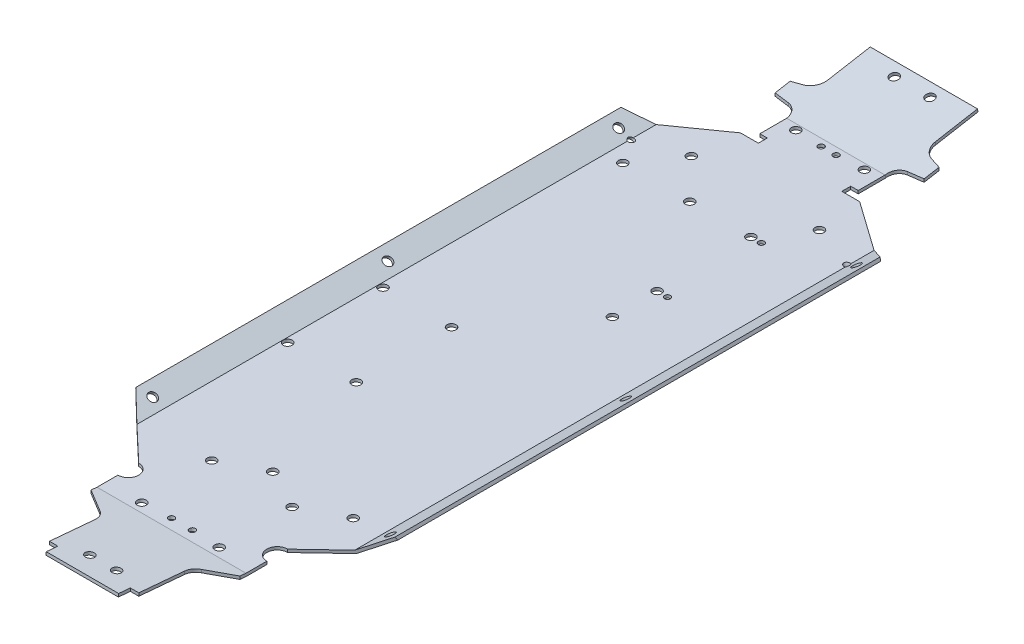
SolidWorks part; units mm, degrees
ref_plane "Front Plane" through (0, 0, 0) normal (0, 0, 1) x (1, 0, 0)
ref_plane "Top Plane" through (0, 0, 0) normal (0, 1, 0) x (1, 0, 0)
ref_plane "Right Plane" through (0, 0, 0) normal (1, 0, 0) x (0, 0, -1)
sketch "Sketch1" plane through (0, 0, 0) normal (0, 0, 1) x (1, 0, 0)
  line L0 (0, 0) -> (7.1603, -4.134)
  line L1 (7.1603, -4.134) -> (80.8397, -4.134)
  line L2 (80.8397, -4.134) -> (88, 0)
  line L3 (0.5, 0.866) -> (7.4282, -3.134)
  line L4 (7.4282, -3.134) -> (80.5718, -3.134)
  line L5 (80.5718, -3.134) -> (87.5, 0.866)
  line L6 (0, 0) -> (0.5, 0.866)
  line L7 (88, 0) -> (87.5, 0.866)
  dimension "D1" = 88
  dimension "D3" = 5
  dimension "D4" = 150
  dimension "D2" = 1
extrude "Boss-Extrude1" add sketch "Sketch1" along normal blind 197
sketch "Sketch3" plane through (0, -3.134, 0) normal (0, 1, 0) x (1, 0, 0)
  line L0 (24, 0) -> (44, 0) construction
  line L1 (0, -179) -> (0, -17)
  line L2 (88, -17) -> (64, 0)
  line L3 (0, -197) -> (0, 0) construction
  line L4 (88, -17) -> (44, -17) construction
  line L5 (44, 3.5664) -> (44, -208.1457) construction
  line L6 (0, -17) -> (24, 0)
  line L7 (24, 0) -> (64, 0)
  line L8 (0, -179) -> (19, -197)
  line L9 (80.5718, -197) -> (7.4282, -197) construction
  line L10 (88, -179) -> (88, -17)
  line L11 (88, -197) -> (88, 0) construction
  line L12 (19, -197) -> (69, -197)
  line L13 (88, -179) -> (69, -197)
  line L14 (0, -17) -> (0, 0)
  line L15 (80.5718, 0) -> (7.4282, 0) construction
  line L17 (0, 0) -> (24, 0)
  line L18 (88, 0) -> (64, 0)
  line L19 (88, 0) -> (88, -17)
  line L20 (0, -179) -> (0, -197)
  line L21 (0, -197) -> (19, -197)
  line L22 (69, -197) -> (88, -197)
  line L23 (88, -197) -> (88, -179)
  point P26 (44, -197)
  line M5 (80.5718, 0) -> (7.4282, 0)
  line M6 (7.4282, 0) -> (7.4282, -197)
  line M7 (7.4282, -197) -> (80.5718, -197)
  line M8 (80.5718, -197) -> (80.5718, 0)
  dimension "D2" = 20
  dimension "D3" = 17
  dimension "D4" = 43.5
  dimension "D5" = 18
  dimension "D6" = 25
extrude "Cut-Extrude3" cut sketch "Sketch3" against normal through all both and the other way through all contours L17 L14 L6 M6 | L6 M6 M5 | L2 M8 M5 | L19 L18 L2 M8 | L20 L21 L8 M6 | L8 M6 M7 | L13 M8 M7 | L22 L23 L13 M8
sketch "Sketch5" plane through (0, 0, 0) normal (1, 0, 0) x (0, 0, -1)
  line L0 (0, -3.134) -> (12, -3.134)
  line L1 (12, -3.134) -> (41.5442, 2.0755)
  line L2 (0, -4.134) -> (12.0875, -4.134)
  line L3 (12.0875, -4.134) -> (41.7179, 1.0907)
  line L4 (0, -3.134) -> (0, -4.134)
  line L5 (41.5442, 2.0755) -> (41.7179, 1.0907)
  dimension "D1" = 12
  dimension "D2" = 170
  dimension "D3" = 30
  dimension "D4" = 1
extrude "Boss-Extrude2" add sketch "Sketch5" along normal up to vertex (88 mm away) up to point (88, -3.134, 0)
sketch "Sketch6" plane through (0, -3.134, 0) normal (0, 1, 0) x (1, 0, 0)
  line L6 (24, 0) -> (30, 0)
  line L7 (24, 0) -> (-1.3455, 0)
  line L9 (44, 41.5442) -> (44, 3.5664) construction
  line L10 (88, 41.7179) -> (0, 41.7179) construction
  line L12 (88, 12.0875) -> (0, 12.0875) construction
  line L31 (30, 0) -> (30, 3)
  line L32 (30, 3) -> (27.5, 3)
  line L33 (27.5, 3) -> (27.5, 12.0875)
  line L34 (23.966, 16.0603) -> (19, 16.6427)
  line L35 (19, 16.6427) -> (19, 21.6427)
  line L36 (19, 21.6427) -> (22.3667, 22.5994)
  line L37 (26, 27.409) -> (26, 41.7179)
  line L38 (24, 0) -> (30, 0)
  line L39 (-1.3455, 0) -> (-1.3455, 57.6061)
  line L40 (-1.3455, 57.6061) -> (89.3455, 57.6061)
  line L41 (44, 41.7179) -> (44, 57.6061)
  line L42 (26, 41.7179) -> (62, 41.7179)
  line L43 (89.3455, 0) -> (89.3455, 57.6061)
  line L44 (64, 0) -> (58, 0)
  line L45 (62, 27.409) -> (62, 41.7179)
  line L46 (69, 21.6427) -> (65.6333, 22.5994)
  line L47 (69, 16.6427) -> (69, 21.6427)
  line L48 (64.034, 16.0603) -> (69, 16.6427)
  line L49 (60.5, 3) -> (60.5, 12.0875)
  line L50 (58, 3) -> (60.5, 3)
  line L51 (58, 0) -> (58, 3)
  line L52 (64, 0) -> (89.3455, 0)
  line L53 (64, 0) -> (58, 0)
  arc A4 (27.5, 12.0875) -> (23.966, 16.0603) centre (23.5, 12.0875) ccw
  arc A5 (22.3667, 22.5994) -> (26, 27.409) centre (21, 27.409) ccw
  arc A6 (65.6333, 22.5994) -> (62, 27.409) centre (67, 27.409) cw
  arc A7 (60.5, 12.0875) -> (64.034, 16.0603) centre (64.5, 12.0875) cw
  point P36 (44, 41.7179)
  dimension "D3" = 5
  dimension "D7" = 5
  dimension "D4" = 4
  dimension "D1" = 3
  dimension "D2" = 2.5
  dimension "D5" = 5
  dimension "D6" = 14
  dimension "D8" = 18
  dimension "D9" = 25
  dimension "D10" = 3.5
extrude "Cut-Extrude4" cut sketch "Sketch6" against normal through all both and the other way through all
sketch "Sketch8" plane through (0, 0, 0) normal (1, 0, 0) x (0, 0, -1)
  line L0 (-197, -3.134) -> (-211, -3.134)
  line L1 (-211, -3.134) -> (-240.8858, -0.5193)
  line L2 (-197, -4.134) -> (-211.0437, -4.134)
  line L3 (-211.0437, -4.134) -> (-240.973, -1.5155)
  line L4 (-197, -3.134) -> (-197, -4.134)
  line L5 (-240.8858, -0.5193) -> (-240.973, -1.5155)
  dimension "D1" = 30
  dimension "D2" = 175
  dimension "D3" = 14
  dimension "D4" = 1
extrude "Boss-Extrude3" add sketch "Sketch8" along normal up to vertex (88 mm away) up to point (88, -3.134, 179)
sketch "Sketch9" plane through (0, -3.134, 0) normal (0, 1, 0) x (1, 0, 0)
  line L0 (29, -221.6085) -> (29, -236.973)
  line L1 (19, -204) -> (19, -213)
  line L4 (27, -218) -> (19, -213)
  line L5 (29, -236.973) -> (31.8498, -236.973)
  line L6 (31.8498, -236.973) -> (31.8498, -240.973)
  line L7 (88, -240.8858) -> (0, -240.8858) construction
  line L8 (0, -197) -> (19, -197) construction
  line L9 (0, -197) -> (19, -197)
  line L10 (0, -197) -> (0, -211) construction
  line L11 (0, -197) -> (0, -211)
  line L12 (88, -240.973) -> (0, -240.973) construction
  line L13 (0, -211) -> (0, -240.8858) construction
  line L14 (56.1502, -240.8858) -> (31.8498, -240.8858)
  line L15 (0, -211) -> (0, -240.8858)
  line L16 (44, -240.8858) -> (44, -190.0299) construction
  line L18 (88, -211) -> (88, -240.8858)
  line L19 (88, -197) -> (88, -211)
  line L20 (88, -197) -> (69, -197)
  line L21 (56.1502, -236.973) -> (56.1502, -240.973)
  line L22 (59, -236.973) -> (56.1502, -236.973)
  line L23 (61, -218) -> (69, -213)
  line L24 (69, -204) -> (69, -213)
  line L25 (59, -221.6085) -> (59, -236.973)
  line L26 (0, -252.0171) -> (31.8498, -252.0171)
  line L27 (31.8498, -252.0171) -> (31.8498, -240.973)
  line L28 (0, -240.8858) -> (0, -252.0171)
  line L29 (56.1502, -240.973) -> (56.1502, -252.0171)
  line L30 (56.1502, -252.0171) -> (88, -252.0171)
  line L31 (88, -252.0171) -> (88, -240.8858)
  arc A0 (19, -197) -> (19, -204) centre (19, -200.5) cw
  arc A1 (27, -218) -> (29, -221.6085) centre (24.7447, -221.6085) cw
  arc A2 (61, -218) -> (59, -221.6085) centre (63.2553, -221.6085) ccw
  arc A3 (69, -197) -> (69, -204) centre (69, -200.5) ccw
  point P13 (44, -240.8858)
  point P29 (44, -240.8858)
  line M14 (19, -197) -> (0, -197)
  line M15 (0, -197) -> (0, -211)
  line M16 (0, -211) -> (88, -211)
  line M17 (88, -211) -> (88, -197)
  line M18 (88, -197) -> (69, -197)
  dimension "D1" = 3.5
  dimension "D2" = 9
  dimension "D3" = 8
  dimension "D4" = 5
  dimension "D5" = 15
  dimension "D6" = 12.1502
  dimension "D7" = 4
extrude "q" cut sketch "Sketch9" against normal through all both and the other way through all contours L23 A2 L25 L22 L21 L14 L18 L24 M16 | A3 L24 M18 M16 M17 | A1 L4 L1 L15 L14 L6 L5 L0 M16 | A0 L1 M14 M15 M16
sketch "Sketch11" plane through (0, -22.4262, 1.962) normal (0, -0.9962, 0.0872) x (1, 0, 0)
  line L0 (44, 241.7717) -> (44, 200.7065) construction
  line L3 (56.1502, 239.9239) -> (31.8498, 239.9239) construction
  line L4 (25.3426, 205.4239) -> (62.1457, 205.4239) construction
  circle A0 centre (39.5, 232.9239) radius 1.5
  circle A3 centre (31, 206.9239) radius 1.5
  circle A4 centre (40.5, 206.4239) radius 1
  circle A5 centre (47.5, 206.4239) radius 1
  circle A6 centre (57, 206.9239) radius 1.5
  circle A7 centre (48.5, 232.9239) radius 1.5
  point P8 (40.5, 206.4589)
  point P19 (44, 239.9239)
  dimension "D1" = 3
  dimension "D2" = 2
  dimension "D5" = 33
  dimension "D6" = 13
  dimension "D7" = 3.5
  dimension "D3" = 4.5
  dimension "D4" = 7
extrude "Cut-Extrude5" cut sketch "Sketch11" against normal blind 10
sketch "Sketch12" plane through (0, 0, 0) normal (-0.5, -0.866, 0) x (0.866, -0.5, 0)
  line L1 (4.134, 14.4641) -> (4.134, 182.3917) construction
  line L2 (0, 17) -> (8.2679, 11.9282) construction
  line L3 (0, 179) -> (8.2679, 185.7834) construction
  line L4 (8.2679, 185.7834) -> (8.2679, 11.9282) construction
  line L5 (0, 179) -> (0, 17) construction
  line L6 (0, 179) -> (0, 17)
  line L7 (4.134, 19.4641) -> (9.7158, 19.4641) construction
  line L9 (8.2679, 185.7834) -> (0, 179)
  line L10 (0, 179) -> (0, 17)
  line L11 (0, 17) -> (8.2679, 11.9282)
  line L12 (8.2679, 11.9282) -> (8.2679, 185.7834)
  line L13 (8.2679, 185.7834) -> (0, 179)
  line L14 (0, 179) -> (0, 17)
  line L15 (0, 17) -> (8.2679, 11.9282)
  line L16 (8.2679, 11.9282) -> (8.2679, 185.7834)
  circle A0 centre (4.134, 177.3917) radius 1.5
  circle A1 centre (4.134, 98.4279) radius 1.5
  circle A2 centre (4.134, 20.9641) radius 1.5
  circle A3 centre (8.2679, 20.4641) radius 1
  point P8 (8.2679, 20.4384)
  point P12 (4.134, 14.4641)
  point P15 (4.134, 182.3917)
  point P20 (0, 98)
  dimension "D1" = 3
  dimension "D2" = 5
  dimension "D3" = 5
  dimension "D5" = 2
  dimension "D4" = 0
extrude "Cut-Extrude6" cut sketch "Sketch12" against normal blind 10 contours A0 | A1 | A2 | A3
ref_plane "Plane1" through (44, 0, 0) normal (1, 0, 0) x (0, 0, -1)
mirror "Mirror1" about plane through (44, 0, 0) normal (1, 0, 0) of "Cut-Extrude6"
sketch "Sketch14" plane through (0, -4.134, 0) normal (0, -1, 0) x (1, 0, 0)
  line L0 (44, 211.0437) -> (44, -12.0875) construction
  line L1 (69, 211.0437) -> (19, 211.0437) construction
  line L2 (60.5, -12.0875) -> (27.5, -12.0875) construction
  line L3 (30, 0) -> (24, 0) construction
  line L4 (60.5, -12.0875) -> (27.5, -12.0875) construction
  line L5 (55.5, -8.5875) -> (32.5, -8.5875) construction
  line L6 (44, -12.0875) -> (44, -44.7093) construction
  line L7 (-543.5401, -528.8511) -> (-826.2219, -525.6386) construction
  circle A0 centre (30.5, 184) radius 1.5
  circle A1 centre (22.5, 15) radius 1.5
  circle A2 centre (44, 177) radius 1.5
  circle A3 centre (65.5, 15) radius 1.5
  circle A4 centre (57.5, 184) radius 1.5
  circle A5 centre (71, 177) radius 1.5
  circle A6 centre (9, 137) radius 1.5
  circle A7 centre (32, 105) radius 1.5
  circle A8 centre (32, 137) radius 1.5
  circle A9 centre (9, 105) radius 1.5
  circle A12 centre (13, 28.5) radius 1.5
  circle A13 centre (35.5, 28.5) radius 1.5
  circle A14 centre (56, 28.5) radius 1.5
  circle A15 centre (59.5, 28.5) radius 1
  circle A16 centre (56, 75) radius 1.5
  circle A17 centre (56, 60) radius 1.5
  circle A18 centre (55.5, -10.0875) radius 1.5
  circle A19 centre (32.5, -10.0875) radius 1.5
  circle A20 centre (46.5, -9.5875) radius 1
  circle A21 centre (41.5, -9.5875) radius 1
  circle A22 centre (59.5, 60) radius 1
  point P49 (9.2819, 134.842)
  point P54 (30.5, 134.842)
  point P60 (30.5, 102.6198)
  point P61 (9.2819, 102.6198)
  point P62 (0, 0)
  point P63 (54.1182, 73.1926)
  point P64 (54.1182, 58.1772)
  point P65 (0, 0)
  point P66 (9.7912, 134.3029)
  point P67 (9.7912, 102.6198)
  point P68 (32.4116, 102.6198)
  point P69 (58.4875, 58.1772)
  point P70 (46.5, 177)
  point P71 (44, 177)
  point P72 (70.9742, 177)
  point P73 (71, 177)
  point P74 (0, 0)
  point P75 (0, 0)
  point P76 (0, 0)
  point P77 (54.1182, 58.1772)
  point P78 (0, 0)
  point P79 (59.5, 58.1772)
  point P80 (9, 135.5952)
  point P81 (32, 105)
  point P82 (56, 60)
  point P83 (56, 75)
  point P84 (44, 73.8069)
  point P85 (59.5, 60)
  point P86 (56, 75)
  point P87 (56, 75)
  point P88 (59.5, 60)
  dimension "D2" = 3
  dimension "D3" = 43
  dimension "D4" = 13.5
  dimension "D6" = 7
  dimension "D8" = 8.5
  dimension "D10" = 3
  dimension "D11" = 23
  dimension "D12" = 11.5
  dimension "D14" = 2
  dimension "D18" = 2
  dimension "D19" = 3.5
  dimension "D22" = 27
  dimension "D27" = 30
  dimension "D29" = 3
  dimension "D30" = 2
  dimension "D31" = 3.5
  dimension "D1" = 13
  dimension "D5" = 15
  dimension "D7" = 22.5
  dimension "D9" = 28.5
  dimension "D13" = 2
  dimension "D15" = 2.5
  dimension "D16" = 5
  dimension "D17" = 12
  dimension "D20" = 13.5
  dimension "D21" = 282.7
  dimension "D23" = 12
  dimension "D24" = 35
  dimension "D25" = 32
  dimension "D26" = 40
  dimension "D28" = 15
extrude "Cut-Extrude7" cut sketch "Sketch14" against normal blind 10
sketch "Sketch16" plane through (0, -6.0764, -1.0714) normal (0, -0.9848, -0.1736) x (1, 0, 0)
  line L0 (44, -11.186) -> (44, -41.2735) construction
  line L1 (60.5, -11.186) -> (27.5, -11.186) construction
  line L2 (62, -41.2735) -> (26, -41.2735) construction
  circle A0 centre (38, -37.2735) radius 1.5
  circle A1 centre (50, -37.2735) radius 1.5
  point P10 (37.8252, -35.155)
  dimension "D2" = 3
  dimension "D3" = 4
  dimension "D1" = 12
extrude "Cut-Extrude8" cut sketch "Sketch16" against normal blind 10
